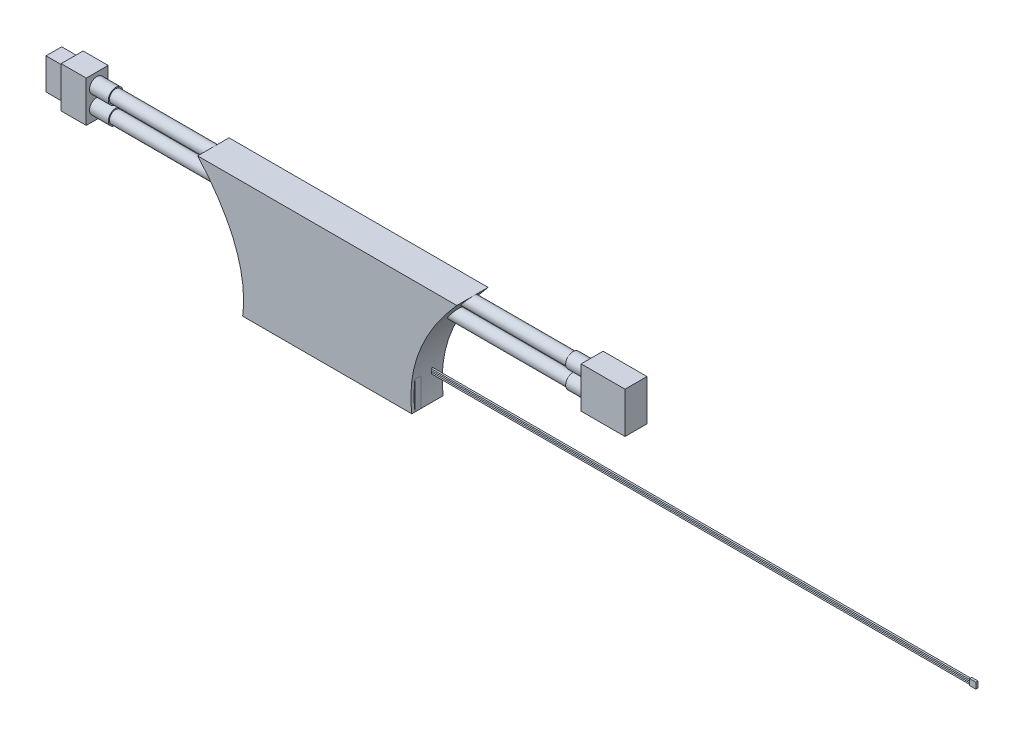
SolidWorks part; units mm, degrees
ref_plane "Front Plane" through (0, 0, 0) normal (0, 0, 1) x (1, 0, 0)
ref_plane "Top Plane" through (0, 0, 0) normal (0, 1, 0) x (1, 0, 0)
ref_plane "Right Plane" through (0, 0, 0) normal (1, 0, 0) x (0, 0, -1)
sketch "Sketch1" plane through (0, 0, 0) normal (0, 0, 1) x (1, 0, 0)
  line L1 (0, 0) -> (27, 0)
  line L2 (0, 0) -> (0, 18)
  line L3 (0, 18) -> (27, 18)
  line L4 (27, 0) -> (27, 18)
  dimension "D1" = 27
  dimension "D2" = 18
extrude "Boss-Extrude8" add sketch "Sketch1" against normal blind 1 contours L3 L4 L1 L2
sketch "Sketch8" plane through (0, 0, -1) normal (0, 0, -1) x (-1, 0, 0)
  line L0 (0, 0) -> (-27, 0) construction
  line L1 (-0.95, 0) -> (-12.95, 0)
  line L2 (-0.95, 0) -> (-0.95, 12)
  line L3 (-0.95, 12) -> (-12.95, 12)
  line L4 (-12.95, 0) -> (-12.95, 12)
  dimension "D1" = 12
  dimension "D2" = 12
extrude "Boss-Extrude10" add sketch "Sketch8" along normal blind 3.5 contours L3 L4 L1 L2
sketch "Sketch9" plane through (27, 0, 0) normal (1, 0, 0) x (0, 0, -1)
  circle A0 centre (2.2367, 17.5692) radius 1
  circle A1 centre (2.2367, 14.695) radius 1
  dimension "D1" = 2
  dimension "D2" = 2
extrude "Boss-Extrude11" add sketch "Sketch9" along normal blind 23 and the other way blind 50 separate body
sketch "Sketch10" plane through (50, 0, 0) normal (1, 0, 0) x (0, 0, -1)
  circle A0 centre (2.2367, 17.5692) radius 1.1791
  circle A1 centre (2.2367, 14.695) radius 1.18
  dimension "D1" = 2.3582
  dimension "D2" = 2.36
extrude "Boss-Extrude12" add sketch "Sketch10" along normal blind 3
sketch "Sketch11" plane through (-23, 0, 0) normal (-1, 0, 0) x (0, 0, 1)
  circle A0 centre (-2.2367, 17.5692) radius 1.18
  circle A1 centre (-2.2367, 14.695) radius 1.18
  dimension "D1" = 2.36
  dimension "D2" = 2.36
extrude "Boss-Extrude13" add sketch "Sketch11" along normal blind 3
sketch "Sketch12" plane through (53, 0, 0) normal (1, 0, 0) x (0, 0, -1)
  line L1 (0.531, 19.3941) -> (4.0345, 19.3941)
  line L2 (0.531, 19.3941) -> (0.531, 12.8454)
  line L3 (0.531, 12.8454) -> (4.0345, 12.8454)
  line L4 (4.0345, 19.3941) -> (4.0345, 12.8454)
  dimension "D1" = 6.5487
  dimension "D2" = 3.5035
extrude "Boss-Extrude14" add sketch "Sketch12" along normal blind 7
sketch "Sketch13" plane through (-26, 0, 0) normal (-1, 0, 0) x (0, 0, 1)
  line L1 (-4.0345, 19.3941) -> (-0.5345, 19.3941)
  line L2 (-4.0345, 19.3941) -> (-4.0345, 12.8441)
  line L3 (-4.0345, 12.8441) -> (-0.5345, 12.8441)
  line L4 (-0.5345, 19.3941) -> (-0.5345, 12.8441)
  dimension "D1" = 3.5
  dimension "D2" = 6.55
extrude "Boss-Extrude15" add sketch "Sketch13" along normal blind 4
sketch "Sketch14" plane through (-30, 0, 0) normal (-1, 0, 0) x (0, 0, 1)
  line L1 (-3.612, 18.6827) -> (-1.112, 18.6827)
  line L2 (-3.612, 18.6827) -> (-3.612, 13.6827)
  line L3 (-3.612, 13.6827) -> (-1.112, 13.6827)
  line L4 (-1.112, 18.6827) -> (-1.112, 13.6827)
  dimension "D1" = 5
  dimension "D2" = 2.5
extrude "Boss-Extrude16" add sketch "Sketch14" along normal blind 3
sketch "Sketch15" plane through (12.95, 0, 0) normal (1, 0, 0) x (0, 0, -1)
  line L0 (4.5, 0) -> (1, 0) construction
  circle A0 centre (2.75, 4.69) radius 0.1
  circle A1 centre (2.75, 4.46) radius 0.1
  circle A2 centre (2.75, 4.23) radius 0.1
  circle A3 centre (2.75, 4) radius 0.1
  dimension "D1" = 0.2
  dimension "D2" = 0.2
  dimension "D3" = 0.2
  dimension "D4" = 0.2
  dimension "D5" = 0.23
  dimension "D6" = 0.23
  dimension "D7" = 0.23
  dimension "D8" = 4
extrude "Boss-Extrude20" add sketch "Sketch15" along normal blind 100 contours A0 | A1 | A2 | A3
sketch "Sketch16" plane through (112.95, 0, 0) normal (1, 0, 0) x (0, 0, -1)
  line L1 (2.582, 4.844) -> (2.9209, 4.844)
  line L2 (2.582, 4.844) -> (2.582, 3.8695)
  line L3 (2.582, 3.8695) -> (2.9209, 3.8695)
  line L4 (2.9209, 4.844) -> (2.9209, 3.8695)
extrude "Boss-Extrude21" add sketch "Sketch16" along normal blind 1
sketch "Sketch17" plane through (0, 0, -4.5) normal (0, 0, -1) x (-1, 0, 0)
  line L0 (23, 18.5692) -> (-50, 18.5692) construction
  line L1 (-27, 0) -> (0, 0)
  line L3 (-27, 18.5692) -> (0, 18.5692)
  line L5 (-34.1794, 18.5692) -> (7.1794, 18.5692)
  line L6 (-27, 0) -> (0, 0)
  spline S0 degree 2 poles (-34.1794, 18.5692) (-25.8149, 9.2146) (-27, 0) knots 0 0 0 0.640923 0.640923 0.640923
  spline S1 degree 2 poles (7.1794, 18.5692) (-1.1851, 9.2146) (0, 0) knots 0 0 0 0.640923 0.640923 0.640923
  line M2 (-0.95, 0) -> (-0.95, 12)
  line M3 (-0.95, 12) -> (-12.95, 12)
  line M4 (-12.95, 12) -> (-12.95, 0)
  line M5 (-12.95, 0) -> (-0.95, 0)
extrude "Boss-Extrude22" add sketch "Sketch17" against normal blind 5 separate body contours S1 L5 L3 S0 L1 M4 M3 M2 | M5 M2 M3 M4
